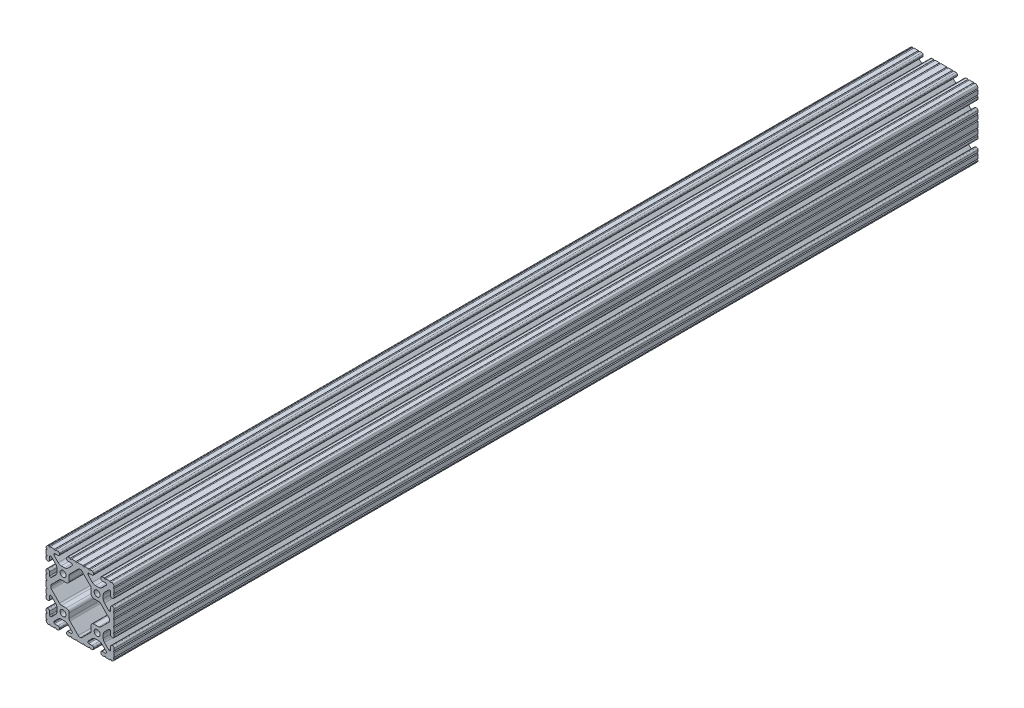
SolidWorks part; units mm, degrees
material "6061-T6 (SS)"
ref_plane "Front Plane" through (0, 0, 0) normal (0, 0, 1) x (1, 0, 0)
ref_plane "Top Plane" through (0, 0, 0) normal (0, 1, 0) x (1, 0, 0)
ref_plane "Right Plane" through (0, 0, 0) normal (1, 0, 0) x (0, 0, -1)
ref_plane "Plane1" through (0, 0, -609.6) normal (0, 0, -1) x (-1, 0, 0)
sketch "Sketch1" plane through (0, 0, -609.6) normal (0, 0, -1) x (-1, 0, 0)
  line L0 (31.9021, -2.4756) -> (23.0141, -11.3637)
  line L1 (20.769, -12.2936) -> (15.4686, -12.2936)
  line L2 (12.2936, -15.4686) -> (12.2936, -20.5983)
  line L3 (11.3637, -22.8433) -> (2.0515, -32.1555)
  line L4 (-2.0515, -32.1555) -> (-11.3637, -22.8433)
  line L5 (-12.2936, -20.5983) -> (-12.2936, -15.4686)
  line L6 (-15.4686, -12.2936) -> (-20.769, -12.2936)
  line L7 (-23.0141, -11.3637) -> (-31.9021, -2.4756)
  line L8 (-31.9021, 2.4756) -> (-23.0141, 11.3637)
  line L9 (-20.769, 12.2936) -> (-15.4686, 12.2936)
  line L10 (-12.2936, 15.4686) -> (-12.2936, 20.5983)
  line L11 (-11.3637, 22.8433) -> (-2.0515, 32.1555)
  line L12 (2.0515, 32.1555) -> (11.3637, 22.8433)
  line L13 (12.2936, 20.5983) -> (12.2936, 15.4686)
  line L14 (15.4686, 12.2936) -> (20.769, 12.2936)
  line L15 (23.0141, 11.3637) -> (31.9021, 2.4756)
  line L16 (36.5252, -23.0554) -> (35.6108, -23.0554)
  line L17 (34.036, -24.6302) -> (34.036, -28.448)
  line L18 (33.147, -29.337) -> (32.6643, -29.337)
  line L19 (32.0357, -29.0766) -> (27.1976, -24.2385)
  line L20 (25.8064, -20.8799) -> (25.8064, -17.2201)
  line L21 (27.1976, -13.8615) -> (31.9489, -9.1101)
  line L22 (32.7869, -8.763) -> (33.0603, -8.763)
  line L23 (34.036, -9.7387) -> (34.036, -13.4698)
  line L24 (35.6108, -15.0446) -> (36.5252, -15.0446)
  line L25 (38.1, -13.4698) -> (38.1, -11.075)
  line L26 (38.1, -9.552) -> (38.1, -4.7238)
  line L27 (38.1, -3.2007) -> (38.1, 3.2007)
  line L28 (38.1, 4.7238) -> (38.1, 9.552)
  line L29 (38.1, 11.075) -> (38.1, 13.4698)
  line L30 (36.5252, 15.0446) -> (35.6108, 15.0446)
  line L31 (34.036, 13.4698) -> (34.036, 9.7387)
  line L32 (33.0603, 8.763) -> (32.7869, 8.763)
  line L33 (31.9489, 9.1101) -> (27.1976, 13.8615)
  line L34 (25.8064, 17.2201) -> (25.8064, 20.8799)
  line L35 (27.1976, 24.2385) -> (32.0357, 29.0766)
  line L36 (32.6643, 29.337) -> (33.147, 29.337)
  line L37 (34.036, 28.448) -> (34.036, 24.6302)
  line L38 (35.6108, 23.0554) -> (36.5252, 23.0554)
  line L39 (38.1, 24.6302) -> (38.1, 27.0238)
  line L40 (38.1, 28.5453) -> (38.1, 33.373)
  line L41 (33.4288, 38.1) -> (28.6011, 38.1)
  line L42 (27.0772, 38.1) -> (24.6888, 38.1)
  line L43 (23.114, 36.5252) -> (23.114, 35.6108)
  line L44 (24.6888, 34.036) -> (28.448, 34.036)
  line L45 (29.337, 33.147) -> (29.337, 32.7207)
  line L46 (29.1002, 31.8885) -> (24.4093, 27.1976)
  line L47 (21.0507, 25.8064) -> (17.0493, 25.8064)
  line L48 (13.6907, 27.1976) -> (9.0234, 31.8649)
  line L49 (8.763, 32.4935) -> (8.763, 33.147)
  line L50 (9.652, 34.036) -> (13.4112, 34.036)
  line L51 (14.986, 35.6108) -> (14.986, 36.5252)
  line L52 (13.4112, 38.1) -> (11.1289, 38.1)
  line L53 (9.6053, 38.1) -> (4.7773, 38.1)
  line L54 (3.2537, 38.1) -> (-3.2537, 38.1)
  line L55 (-4.7773, 38.1) -> (-9.6053, 38.1)
  line L56 (-11.1289, 38.1) -> (-13.4112, 38.1)
  line L57 (-14.986, 36.5252) -> (-14.986, 35.6108)
  line L58 (-13.4112, 34.036) -> (-9.652, 34.036)
  line L59 (-8.763, 33.147) -> (-8.763, 32.4935)
  line L60 (-9.0234, 31.8649) -> (-13.6907, 27.1976)
  line L61 (-17.0493, 25.8064) -> (-21.0507, 25.8064)
  line L62 (-24.4093, 27.1976) -> (-29.1002, 31.8885)
  line L63 (-29.337, 32.7207) -> (-29.337, 33.147)
  line L64 (-28.448, 34.036) -> (-24.6888, 34.036)
  line L65 (-23.114, 35.6108) -> (-23.114, 36.5252)
  line L66 (-24.6888, 38.1) -> (-27.0772, 38.1)
  line L67 (-28.6011, 38.1) -> (-33.4288, 38.1)
  line L68 (-38.1, 33.373) -> (-38.1, 28.5453)
  line L69 (-38.1, 27.0238) -> (-38.1, 24.6302)
  line L70 (-36.5252, 23.0554) -> (-35.6108, 23.0554)
  line L71 (-34.036, 24.6302) -> (-34.036, 28.448)
  line L72 (-33.147, 29.337) -> (-32.6643, 29.337)
  line L73 (-32.0357, 29.0766) -> (-27.1976, 24.2385)
  line L74 (-25.8064, 20.8799) -> (-25.8064, 17.2201)
  line L75 (-27.1976, 13.8615) -> (-31.9489, 9.1101)
  line L76 (-32.7869, 8.763) -> (-33.0603, 8.763)
  line L77 (-34.036, 9.7387) -> (-34.036, 13.4698)
  line L78 (-35.6108, 15.0446) -> (-36.5252, 15.0446)
  line L79 (-38.1, 13.4698) -> (-38.1, 11.075)
  line L80 (-38.1, 9.552) -> (-38.1, 4.7238)
  line L81 (-38.1, 3.2007) -> (-38.1, -3.2007)
  line L82 (-38.1, -4.7238) -> (-38.1, -9.552)
  line L83 (-38.1, -11.075) -> (-38.1, -13.4698)
  line L84 (-36.5252, -15.0446) -> (-35.6108, -15.0446)
  line L85 (-34.036, -13.4698) -> (-34.036, -9.7387)
  line L86 (-33.0603, -8.763) -> (-32.7869, -8.763)
  line L87 (-31.9489, -9.1101) -> (-27.1976, -13.8615)
  line L88 (-25.8064, -17.2201) -> (-25.8064, -20.8799)
  line L89 (-27.1976, -24.2385) -> (-32.0357, -29.0766)
  line L90 (-32.6643, -29.337) -> (-33.147, -29.337)
  line L91 (-34.036, -28.448) -> (-34.036, -24.6302)
  line L92 (-35.6108, -23.0554) -> (-36.5252, -23.0554)
  line L93 (-38.1, -24.6302) -> (-38.1, -27.0238)
  line L94 (-38.1, -28.5453) -> (-38.1, -33.373)
  line L95 (-33.4288, -38.1) -> (-28.6011, -38.1)
  line L96 (-27.0772, -38.1) -> (-24.6888, -38.1)
  line L97 (-23.114, -36.5252) -> (-23.114, -35.6108)
  line L98 (-24.6888, -34.036) -> (-28.448, -34.036)
  line L99 (-29.337, -33.147) -> (-29.337, -32.7207)
  line L100 (-29.1002, -31.8885) -> (-24.4093, -27.1976)
  line L101 (-21.0507, -25.8064) -> (-17.0493, -25.8064)
  line L102 (-13.6907, -27.1976) -> (-9.0234, -31.8649)
  line L103 (-8.763, -32.4935) -> (-8.763, -33.147)
  line L104 (-9.652, -34.036) -> (-13.4112, -34.036)
  line L105 (-14.986, -35.6108) -> (-14.986, -36.5252)
  line L106 (-13.4112, -38.1) -> (-11.1289, -38.1)
  line L107 (-9.6053, -38.1) -> (-4.7773, -38.1)
  line L108 (-3.2537, -38.1) -> (3.2537, -38.1)
  line L109 (4.7773, -38.1) -> (9.6053, -38.1)
  line L110 (11.1289, -38.1) -> (13.4112, -38.1)
  line L111 (14.986, -36.5252) -> (14.986, -35.6108)
  line L112 (13.4112, -34.036) -> (9.652, -34.036)
  line L113 (8.763, -33.147) -> (8.763, -32.4935)
  line L114 (9.0234, -31.8649) -> (13.6907, -27.1976)
  line L115 (17.0493, -25.8064) -> (21.0507, -25.8064)
  line L116 (24.4093, -27.1976) -> (29.1002, -31.8885)
  line L117 (29.337, -32.7207) -> (29.337, -33.147)
  line L118 (28.448, -34.036) -> (24.6888, -34.036)
  line L119 (23.114, -35.6108) -> (23.114, -36.5252)
  line L120 (24.6888, -38.1) -> (27.0772, -38.1)
  line L121 (28.6011, -38.1) -> (33.4288, -38.1)
  line L122 (38.1, -33.373) -> (38.1, -28.5453)
  line L123 (38.1, -27.0238) -> (38.1, -24.6302)
  arc A0 (31.9021, 2.4756) -> (32.7287, 0) centre (29.8367, 0.4102) cw
  arc A1 (32.7287, 0) -> (31.9021, -2.4756) centre (29.8367, -0.4102) cw
  arc A2 (23.0141, -11.3637) -> (20.769, -12.2936) centre (20.769, -9.1186) cw
  arc A3 (15.4686, -12.2936) -> (12.2936, -15.4686) centre (15.4686, -15.4686) ccw
  arc A4 (12.2936, -20.5983) -> (11.3637, -22.8433) centre (9.1186, -20.5983) cw
  arc A5 (2.0515, -32.1555) -> (0, -33.011) centre (-0.0139, -30.09) cw
  arc A6 (0, -33.011) -> (-2.0515, -32.1555) centre (0.0139, -30.09) cw
  arc A7 (-11.3637, -22.8433) -> (-12.2936, -20.5983) centre (-9.1186, -20.5983) cw
  arc A8 (-12.2936, -15.4686) -> (-15.4686, -12.2936) centre (-15.4686, -15.4686) ccw
  arc A9 (-20.769, -12.2936) -> (-23.0141, -11.3637) centre (-20.769, -9.1186) cw
  arc A10 (-31.9021, -2.4756) -> (-32.7287, 0) centre (-29.8367, -0.4102) cw
  arc A11 (-32.7287, 0) -> (-31.9021, 2.4756) centre (-29.8367, 0.4102) cw
  arc A12 (-23.0141, 11.3637) -> (-20.769, 12.2936) centre (-20.769, 9.1186) cw
  arc A13 (-15.4686, 12.2936) -> (-12.2936, 15.4686) centre (-15.4686, 15.4686) ccw
  arc A14 (-12.2936, 20.5983) -> (-11.3637, 22.8433) centre (-9.1186, 20.5983) cw
  arc A15 (-2.0515, 32.1555) -> (0, 33.011) centre (0.0139, 30.09) cw
  arc A16 (0, 33.011) -> (2.0515, 32.1555) centre (-0.0139, 30.09) cw
  arc A17 (11.3637, 22.8433) -> (12.2936, 20.5983) centre (9.1186, 20.5983) cw
  arc A18 (12.2936, 15.4686) -> (15.4686, 12.2936) centre (15.4686, 15.4686) ccw
  arc A19 (20.769, 12.2936) -> (23.0141, 11.3637) centre (20.769, 9.1186) cw
  circle A20 centre (19.05, -19.05) radius 3.3274
  circle A21 centre (19.05, 19.05) radius 3.3274
  circle A22 centre (-19.05, 19.05) radius 3.3274
  circle A23 centre (-19.05, -19.05) radius 3.3274
  arc A24 (38.1, -24.6302) -> (36.5252, -23.0554) centre (36.5252, -24.6302) ccw
  arc A25 (35.6108, -23.0554) -> (34.036, -24.6302) centre (35.6108, -24.6302) ccw
  arc A26 (34.036, -28.448) -> (33.147, -29.337) centre (33.147, -28.448) cw
  arc A27 (32.6643, -29.337) -> (32.0357, -29.0766) centre (32.6643, -28.448) cw
  arc A28 (27.1976, -24.2385) -> (25.8064, -20.8799) centre (30.5562, -20.8799) cw
  arc A29 (25.8064, -17.2201) -> (27.1976, -13.8615) centre (30.5562, -17.2201) cw
  arc A30 (31.9489, -9.1101) -> (32.7869, -8.763) centre (32.7869, -9.9481) cw
  arc A31 (33.0603, -8.763) -> (34.036, -9.7387) centre (33.0603, -9.7387) cw
  arc A32 (34.036, -13.4698) -> (35.6108, -15.0446) centre (35.6108, -13.4698) ccw
  arc A33 (36.5252, -15.0446) -> (38.1, -13.4698) centre (36.5252, -13.4698) ccw
  arc A34 (38.1, -11.075) -> (38.1, -9.552) centre (37.9035, -10.3135) cw
  arc A35 (38.1, -4.7238) -> (38.1, -3.2007) centre (37.9035, -3.9622) cw
  arc A36 (38.1, 3.2007) -> (38.1, 4.7238) centre (37.9035, 3.9622) cw
  arc A37 (38.1, 9.552) -> (38.1, 11.075) centre (37.9035, 10.3135) cw
  arc A38 (38.1, 13.4698) -> (36.5252, 15.0446) centre (36.5252, 13.4698) ccw
  arc A39 (35.6108, 15.0446) -> (34.036, 13.4698) centre (35.6108, 13.4698) ccw
  arc A40 (34.036, 9.7387) -> (33.0603, 8.763) centre (33.0603, 9.7387) cw
  arc A41 (32.7869, 8.763) -> (31.9489, 9.1101) centre (32.7869, 9.9481) cw
  arc A42 (27.1976, 13.8615) -> (25.8064, 17.2201) centre (30.5562, 17.2201) cw
  arc A43 (25.8064, 20.8799) -> (27.1976, 24.2385) centre (30.5562, 20.8799) cw
  arc A44 (32.0357, 29.0766) -> (32.6643, 29.337) centre (32.6643, 28.448) cw
  arc A45 (33.147, 29.337) -> (34.036, 28.448) centre (33.147, 28.448) cw
  arc A46 (34.036, 24.6302) -> (35.6108, 23.0554) centre (35.6108, 24.6302) ccw
  arc A47 (36.5252, 23.0554) -> (38.1, 24.6302) centre (36.5252, 24.6302) ccw
  arc A48 (38.1, 27.0238) -> (38.1, 28.5453) centre (37.9035, 27.7845) cw
  arc A49 (38.1, 33.373) -> (38.1, 34.8455) centre (37.9035, 34.1092) cw
  arc A50 (38.1, 34.8455) -> (37.0861, 37.1826) centre (34.925, 34.8566) ccw
  arc A51 (37.0861, 37.1826) -> (34.9527, 38.1) centre (34.8521, 34.9266) ccw
  arc A52 (34.9527, 38.1) -> (33.4288, 38.1) centre (34.1907, 38.0824) cw
  arc A53 (28.6011, 38.1) -> (27.0772, 38.1) centre (27.8392, 38.0824) cw
  arc A54 (24.6888, 38.1) -> (23.114, 36.5252) centre (24.6888, 36.5252) ccw
  arc A55 (23.114, 35.6108) -> (24.6888, 34.036) centre (24.6888, 35.6108) ccw
  arc A56 (28.448, 34.036) -> (29.337, 33.147) centre (28.448, 33.147) cw
  arc A57 (29.337, 32.7207) -> (29.1002, 31.8885) centre (28.4716, 32.5172) cw
  arc A58 (24.4093, 27.1976) -> (21.0507, 25.8064) centre (21.0507, 30.5562) cw
  arc A59 (17.0493, 25.8064) -> (13.6907, 27.1976) centre (17.0493, 30.5562) cw
  arc A60 (9.0234, 31.8649) -> (8.763, 32.4935) centre (9.652, 32.4935) cw
  arc A61 (8.763, 33.147) -> (9.652, 34.036) centre (9.652, 33.147) cw
  arc A62 (13.4112, 34.036) -> (14.986, 35.6108) centre (13.4112, 35.6108) ccw
  arc A63 (14.986, 36.5252) -> (13.4112, 38.1) centre (13.4112, 36.5252) ccw
  arc A64 (11.1289, 38.1) -> (9.6053, 38.1) centre (10.3671, 38.0824) cw
  arc A65 (4.7773, 38.1) -> (3.2537, 38.1) centre (4.0155, 38.0824) cw
  arc A66 (-3.2537, 38.1) -> (-4.7773, 38.1) centre (-4.0155, 38.0824) cw
  arc A67 (-9.6053, 38.1) -> (-11.1289, 38.1) centre (-10.3671, 38.0824) cw
  arc A68 (-13.4112, 38.1) -> (-14.986, 36.5252) centre (-13.4112, 36.5252) ccw
  arc A69 (-14.986, 35.6108) -> (-13.4112, 34.036) centre (-13.4112, 35.6108) ccw
  arc A70 (-9.652, 34.036) -> (-8.763, 33.147) centre (-9.652, 33.147) cw
  arc A71 (-8.763, 32.4935) -> (-9.0234, 31.8649) centre (-9.652, 32.4935) cw
  arc A72 (-13.6907, 27.1976) -> (-17.0493, 25.8064) centre (-17.0493, 30.5562) cw
  arc A73 (-21.0507, 25.8064) -> (-24.4093, 27.1976) centre (-21.0507, 30.5562) cw
  arc A74 (-29.1002, 31.8885) -> (-29.337, 32.7207) centre (-28.4716, 32.5172) cw
  arc A75 (-29.337, 33.147) -> (-28.448, 34.036) centre (-28.448, 33.147) cw
  arc A76 (-24.6888, 34.036) -> (-23.114, 35.6108) centre (-24.6888, 35.6108) ccw
  arc A77 (-23.114, 36.5252) -> (-24.6888, 38.1) centre (-24.6888, 36.5252) ccw
  arc A78 (-27.0772, 38.1) -> (-28.6011, 38.1) centre (-27.8392, 38.0824) cw
  arc A79 (-33.4288, 38.1) -> (-34.9527, 38.1) centre (-34.1907, 38.0824) cw
  arc A80 (-34.9527, 38.1) -> (-37.0861, 37.1826) centre (-34.8521, 34.9266) ccw
  arc A81 (-37.0861, 37.1826) -> (-38.1, 34.8455) centre (-34.925, 34.8566) ccw
  arc A82 (-38.1, 34.8455) -> (-38.1, 33.373) centre (-37.9035, 34.1092) cw
  arc A83 (-38.1, 28.5453) -> (-38.1, 27.0238) centre (-37.9035, 27.7845) cw
  arc A84 (-38.1, 24.6302) -> (-36.5252, 23.0554) centre (-36.5252, 24.6302) ccw
  arc A85 (-35.6108, 23.0554) -> (-34.036, 24.6302) centre (-35.6108, 24.6302) ccw
  arc A86 (-34.036, 28.448) -> (-33.147, 29.337) centre (-33.147, 28.448) cw
  arc A87 (-32.6643, 29.337) -> (-32.0357, 29.0766) centre (-32.6643, 28.448) cw
  arc A88 (-27.1976, 24.2385) -> (-25.8064, 20.8799) centre (-30.5562, 20.8799) cw
  arc A89 (-25.8064, 17.2201) -> (-27.1976, 13.8615) centre (-30.5562, 17.2201) cw
  arc A90 (-31.9489, 9.1101) -> (-32.7869, 8.763) centre (-32.7869, 9.9481) cw
  arc A91 (-33.0603, 8.763) -> (-34.036, 9.7387) centre (-33.0603, 9.7387) cw
  arc A92 (-34.036, 13.4698) -> (-35.6108, 15.0446) centre (-35.6108, 13.4698) ccw
  arc A93 (-36.5252, 15.0446) -> (-38.1, 13.4698) centre (-36.5252, 13.4698) ccw
  arc A94 (-38.1, 11.075) -> (-38.1, 9.552) centre (-37.9035, 10.3135) cw
  arc A95 (-38.1, 4.7238) -> (-38.1, 3.2007) centre (-37.9035, 3.9622) cw
  arc A96 (-38.1, -3.2007) -> (-38.1, -4.7238) centre (-37.9035, -3.9622) cw
  arc A97 (-38.1, -9.552) -> (-38.1, -11.075) centre (-37.9035, -10.3135) cw
  arc A98 (-38.1, -13.4698) -> (-36.5252, -15.0446) centre (-36.5252, -13.4698) ccw
  arc A99 (-35.6108, -15.0446) -> (-34.036, -13.4698) centre (-35.6108, -13.4698) ccw
  arc A100 (-34.036, -9.7387) -> (-33.0603, -8.763) centre (-33.0603, -9.7387) cw
  arc A101 (-32.7869, -8.763) -> (-31.9489, -9.1101) centre (-32.7869, -9.9481) cw
  arc A102 (-27.1976, -13.8615) -> (-25.8064, -17.2201) centre (-30.5562, -17.2201) cw
  arc A103 (-25.8064, -20.8799) -> (-27.1976, -24.2385) centre (-30.5562, -20.8799) cw
  arc A104 (-32.0357, -29.0766) -> (-32.6643, -29.337) centre (-32.6643, -28.448) cw
  arc A105 (-33.147, -29.337) -> (-34.036, -28.448) centre (-33.147, -28.448) cw
  arc A106 (-34.036, -24.6302) -> (-35.6108, -23.0554) centre (-35.6108, -24.6302) ccw
  arc A107 (-36.5252, -23.0554) -> (-38.1, -24.6302) centre (-36.5252, -24.6302) ccw
  arc A108 (-38.1, -27.0238) -> (-38.1, -28.5453) centre (-37.9035, -27.7845) cw
  arc A109 (-38.1, -33.373) -> (-38.1, -34.8455) centre (-37.9035, -34.1092) cw
  arc A110 (-38.1, -34.8455) -> (-37.0861, -37.1826) centre (-34.925, -34.8566) ccw
  arc A111 (-37.0861, -37.1826) -> (-34.9527, -38.1) centre (-34.8521, -34.9266) ccw
  arc A112 (-34.9527, -38.1) -> (-33.4288, -38.1) centre (-34.1907, -38.0824) cw
  arc A113 (-28.6011, -38.1) -> (-27.0772, -38.1) centre (-27.8392, -38.0824) cw
  arc A114 (-24.6888, -38.1) -> (-23.114, -36.5252) centre (-24.6888, -36.5252) ccw
  arc A115 (-23.114, -35.6108) -> (-24.6888, -34.036) centre (-24.6888, -35.6108) ccw
  arc A116 (-28.448, -34.036) -> (-29.337, -33.147) centre (-28.448, -33.147) cw
  arc A117 (-29.337, -32.7207) -> (-29.1002, -31.8885) centre (-28.4716, -32.5172) cw
  arc A118 (-24.4093, -27.1976) -> (-21.0507, -25.8064) centre (-21.0507, -30.5562) cw
  arc A119 (-17.0493, -25.8064) -> (-13.6907, -27.1976) centre (-17.0493, -30.5562) cw
  arc A120 (-9.0234, -31.8649) -> (-8.763, -32.4935) centre (-9.652, -32.4935) cw
  arc A121 (-8.763, -33.147) -> (-9.652, -34.036) centre (-9.652, -33.147) cw
  arc A122 (-13.4112, -34.036) -> (-14.986, -35.6108) centre (-13.4112, -35.6108) ccw
  arc A123 (-14.986, -36.5252) -> (-13.4112, -38.1) centre (-13.4112, -36.5252) ccw
  arc A124 (-11.1289, -38.1) -> (-9.6053, -38.1) centre (-10.3671, -38.0824) cw
  arc A125 (-4.7773, -38.1) -> (-3.2537, -38.1) centre (-4.0155, -38.0824) cw
  arc A126 (3.2537, -38.1) -> (4.7773, -38.1) centre (4.0155, -38.0824) cw
  arc A127 (9.6053, -38.1) -> (11.1289, -38.1) centre (10.3671, -38.0824) cw
  arc A128 (13.4112, -38.1) -> (14.986, -36.5252) centre (13.4112, -36.5252) ccw
  arc A129 (14.986, -35.6108) -> (13.4112, -34.036) centre (13.4112, -35.6108) ccw
  arc A130 (9.652, -34.036) -> (8.763, -33.147) centre (9.652, -33.147) cw
  arc A131 (8.763, -32.4935) -> (9.0234, -31.8649) centre (9.652, -32.4935) cw
  arc A132 (13.6907, -27.1976) -> (17.0493, -25.8064) centre (17.0493, -30.5562) cw
  arc A133 (21.0507, -25.8064) -> (24.4093, -27.1976) centre (21.0507, -30.5562) cw
  arc A134 (29.1002, -31.8885) -> (29.337, -32.7207) centre (28.4716, -32.5172) cw
  arc A135 (29.337, -33.147) -> (28.448, -34.036) centre (28.448, -33.147) cw
  arc A136 (24.6888, -34.036) -> (23.114, -35.6108) centre (24.6888, -35.6108) ccw
  arc A137 (23.114, -36.5252) -> (24.6888, -38.1) centre (24.6888, -36.5252) ccw
  arc A138 (27.0772, -38.1) -> (28.6011, -38.1) centre (27.8392, -38.0824) cw
  arc A139 (33.4288, -38.1) -> (34.9527, -38.1) centre (34.1907, -38.0824) cw
  arc A140 (34.9527, -38.1) -> (37.0861, -37.1826) centre (34.8521, -34.9266) ccw
  arc A141 (37.0861, -37.1826) -> (38.1, -34.8455) centre (34.925, -34.8566) ccw
  arc A142 (38.1, -34.8455) -> (38.1, -33.373) centre (37.9035, -34.1092) cw
  arc A143 (38.1, -28.5453) -> (38.1, -27.0238) centre (37.9035, -27.7845) cw
extrude "Boss-Extrude1" add sketch "Sketch1" against normal blind 965.2
